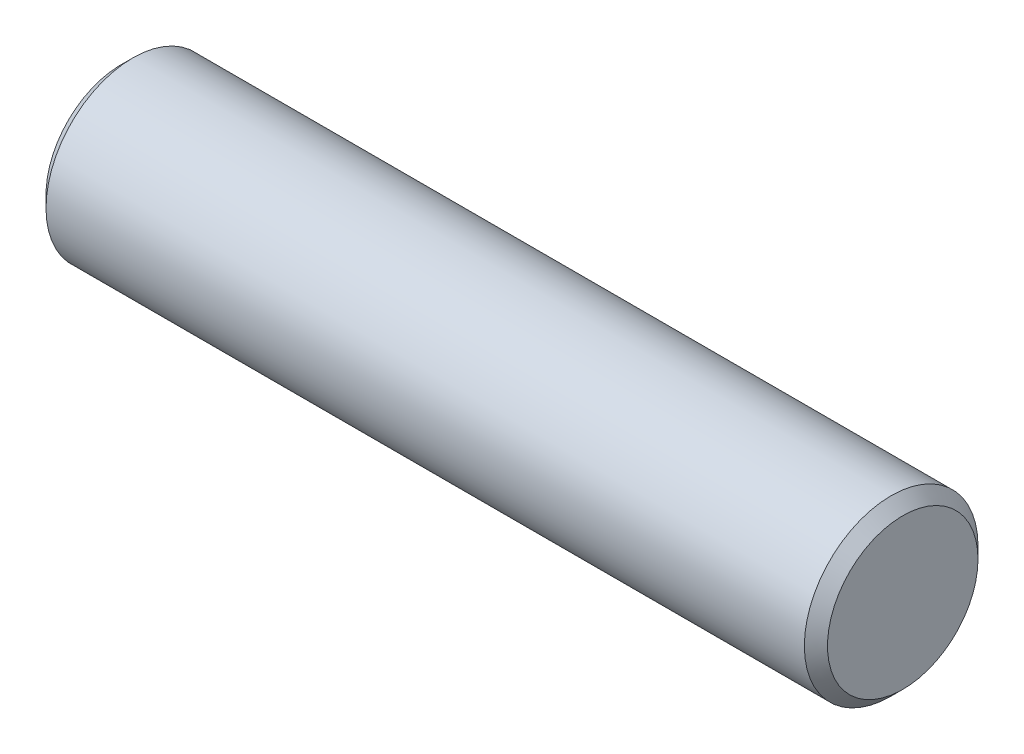
SolidWorks part; units mm, degrees
ref_plane "Front Plane" through (0, 0, 0) normal (0, 0, 1) x (1, 0, 0)
ref_plane "Top Plane" through (0, 0, 0) normal (0, 1, 0) x (1, 0, 0)
ref_plane "Right Plane" through (0, 0, 0) normal (1, 0, 0) x (0, 0, -1)
sketch "Sketch1" plane through (0, 0, 0) normal (1, 0, 0) x (0, 0, -1)
  circle A0 centre (0, 0) radius 1.5
  dimension "D1" = 3
extrude "Boss-Extrude1" add sketch "Sketch1" along normal mid plane 13.5
chamfer "Chamfer1" distance 0.2 angle 45 2 edges at (-6.75, 0, -1.5) (6.75, 0, -1.5)
